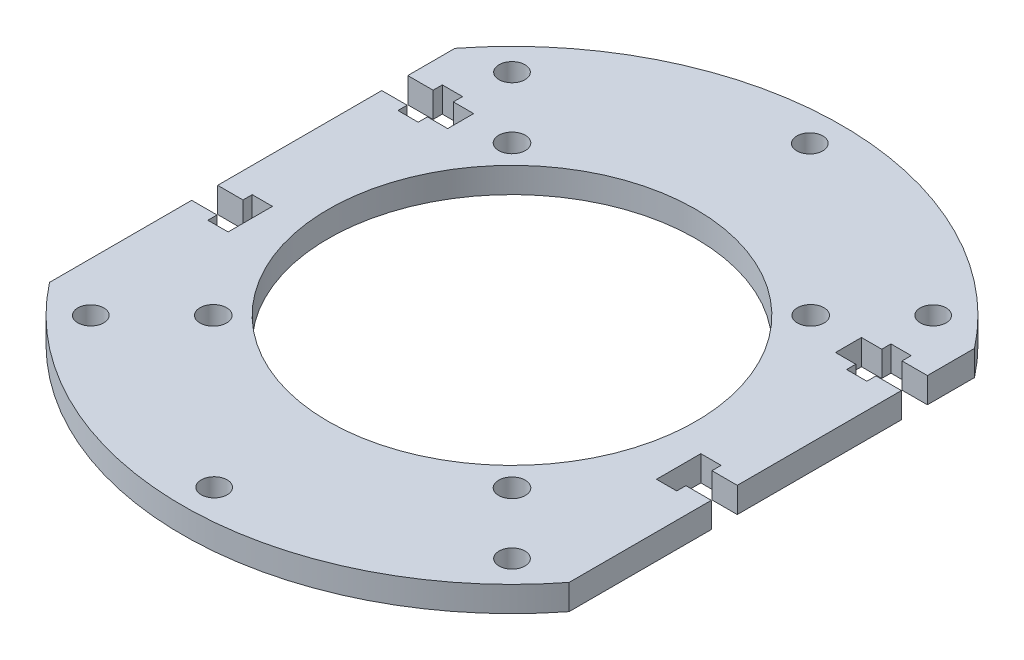
SolidWorks part; units mm, degrees
ref_plane "前视基准面" through (0, 0, 0) normal (0, 0, 1) x (1, 0, 0)
ref_plane "上视基准面" through (0, 0, 0) normal (0, 1, 0) x (1, 0, 0)
ref_plane "右视基准面" through (0, 0, 0) normal (1, 0, 0) x (0, 0, -1)
sketch "草图1" plane through (0, 0, 0) normal (0, 1, 0) x (1, 0, 0)
  line L0 (37, -9.55) -> (37, -11)
  line L1 (23.57, 23.57) -> (-23.57, 23.57) construction
  line L2 (23.57, 23.57) -> (23.57, -23.57) construction
  line L3 (23.57, -23.57) -> (-23.57, -23.57) construction
  line L4 (-23.57, 23.57) -> (-23.57, -23.57) construction
  line L5 (37, -11) -> (33.8, -11)
  line L6 (33.8, -11) -> (33.8, -9.55)
  line L7 (33.8, -5.45) -> (33.8, -4)
  line L8 (37, -4) -> (37, -5.45)
  line L9 (33.8, -4) -> (37, -4)
  line L12 (37, -4) -> (37, 26) construction
  line L13 (37, 20.45) -> (37, 19)
  line L14 (37, 19) -> (33.8, 19)
  line L15 (33.8, 19) -> (33.8, 20.45)
  line L16 (33.8, 24.55) -> (33.8, 26)
  line L17 (37, 26) -> (37, 24.55)
  line L18 (33.8, 26) -> (37, 26)
  line L21 (0, -47) -> (0, -44.95) construction
  line L22 (-37, -4) -> (-37, 26) construction
  line L25 (-33.8, 26) -> (-37, 26)
  line L26 (-37, 26) -> (-37, 24.55)
  line L27 (-33.8, 24.55) -> (-33.8, 26)
  line L28 (-33.8, 19) -> (-33.8, 20.45)
  line L29 (-37, 19) -> (-33.8, 19)
  line L30 (-37, 20.45) -> (-37, 19)
  line L33 (-33.8, -4) -> (-37, -4)
  line L34 (-37, -4) -> (-37, -5.45)
  line L35 (-33.8, -5.45) -> (-33.8, -4)
  line L36 (-33.8, -11) -> (-33.8, -9.55)
  line L37 (-37, -11) -> (-33.8, -11)
  line L38 (-37, -9.55) -> (-37, -11)
  line L39 (37, 24.55) -> (41, 24.55)
  line L40 (41, 24.55) -> (41, 20.45)
  line L41 (41, 20.45) -> (37, 20.45)
  line L42 (33.8, 24.55) -> (30.6, 24.55)
  line L43 (30.6, 24.55) -> (30.6, 20.45)
  line L44 (30.6, 20.45) -> (33.8, 20.45)
  line L45 (37, -5.45) -> (41, -5.45)
  line L46 (41, -5.45) -> (41, -9.55)
  line L47 (41, -9.55) -> (37, -9.55)
  line L48 (33.8, -9.55) -> (30.6, -9.55) construction
  line L49 (30.6, -9.55) -> (30.6, -5.45) construction
  line L50 (30.6, -5.45) -> (33.8, -5.45) construction
  line L51 (-37, 24.55) -> (-41, 24.55)
  line L52 (-41, 24.55) -> (-41, 20.45)
  line L53 (-41, 20.45) -> (-37, 20.45)
  line L54 (-37, -5.45) -> (-41, -5.45)
  line L55 (-41, -5.45) -> (-41, -9.55)
  line L56 (-41, -9.55) -> (-37, -9.55)
  line L57 (-33.8, -5.45) -> (-30.6, -5.45) construction
  line L58 (-30.6, -5.45) -> (-30.6, -9.55) construction
  line L59 (-30.6, -9.55) -> (-33.8, -9.55) construction
  line L60 (-33.8, 24.55) -> (-30.6, 24.55)
  line L61 (-30.6, 24.55) -> (-30.6, 20.45)
  line L62 (-30.6, 20.45) -> (-33.8, 20.45)
  line L63 (-33.8, -9.55) -> (-33.8, -5.45)
  line L64 (33.8, -9.55) -> (33.8, -5.45)
  circle A0 centre (0, 0) radius 29
  circle A1 centre (0, 0) radius 52
  circle A2 centre (47, 0) radius 2.05
  circle A3 centre (33.234, -33.234) radius 2.05
  circle A4 centre (0, -47) radius 2.05
  circle A5 centre (-33.234, -33.234) radius 2.05
  circle A6 centre (-47, 0) radius 2.05
  circle A7 centre (-33.234, 33.234) radius 2.05
  circle A8 centre (0, 47) radius 2.05
  circle A9 centre (33.234, 33.234) radius 2.05
  circle A10 centre (0, 0) radius 43 construction
  circle A11 centre (-23.57, 23.57) radius 2.1
  circle A12 centre (-23.57, -23.57) radius 2.1
  circle A13 centre (23.57, -23.57) radius 2.1
  circle A14 centre (23.57, 23.57) radius 2.1
  circle A15 centre (0, 0) radius 25 construction
  circle A16 centre (0, 0) radius 9.5 construction
  point P6 (52, 0)
  point P9 (43, 0)
  dimension "D1" = 58
  dimension "D2" = 86
  dimension "D3" = 4
  dimension "D4" = 4.1
  dimension "D6" = 30
  dimension "D7" = 5
  dimension "D5" = 8
extrude "凸台-拉伸1" add sketch "草图1" along normal blind 4
sketch "草图2" plane through (0, 4, 0) normal (0, 1, 0) x (1, 0, 0)
  line L1 (-41, -55.0176) -> (41, -55.0176)
  line L2 (-41, -55.0176) -> (-41, 55.0176)
  line L3 (-41, 55.0176) -> (41, 55.0176)
  line L4 (41, -55.0176) -> (41, 55.0176)
  line L5 (-41, -55.0176) -> (41, 55.0176) construction
  line L6 (-41, 55.0176) -> (41, -55.0176) construction
  point P0 (0, 0)
  dimension "D1" = 82
extrude "切除-拉伸-薄壁1" cut sketch "草图2" against normal blind 4 thin
